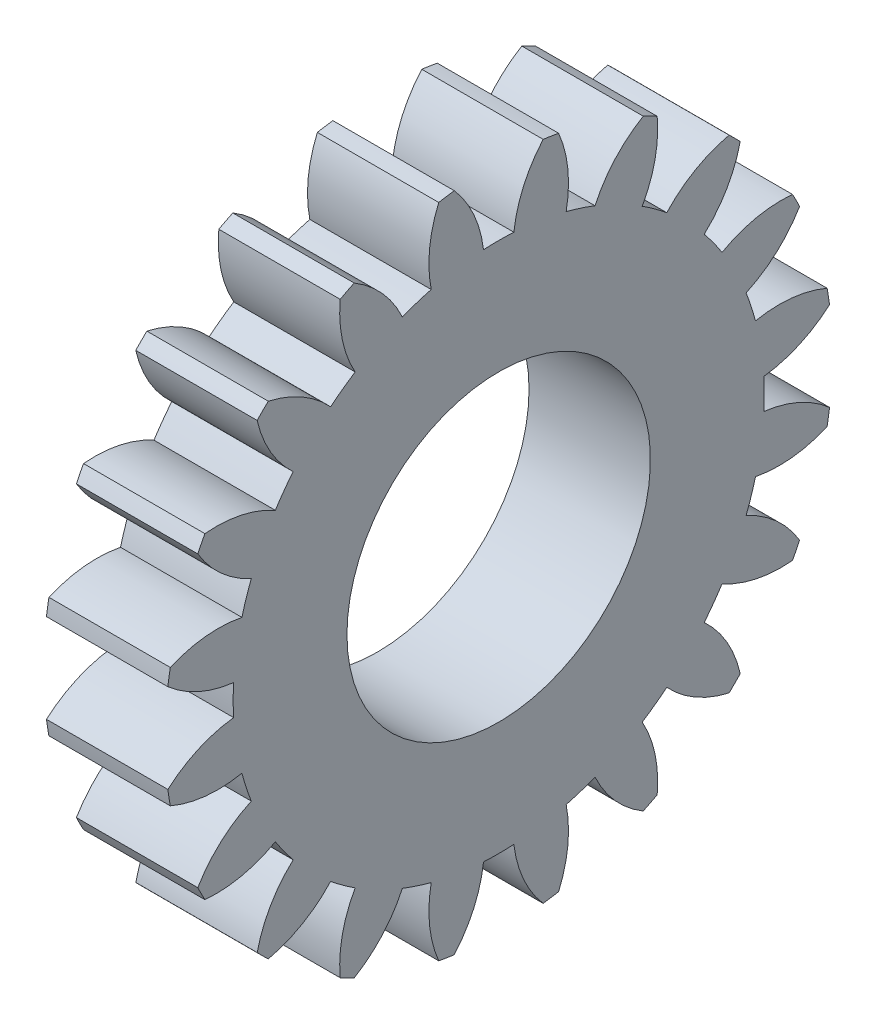
SolidWorks part; units mm, degrees
ref_plane "Plane1" through (0, 0, 0) normal (0, 0, 1) x (1, 0, 0)
ref_plane "Plane2" through (0, 0, 0) normal (0, 1, 0) x (1, 0, 0)
ref_plane "Plane3" through (0, 0, 0) normal (1, 0, 0) x (0, 0, -1)
sketch "HoldingSke" plane through (0, 0, 0) normal (0, 1, 0) x (1, 0, 0)
  line L0 (0, 0) -> (0.9397, -0.342)
  line L1 (-15, 0) -> (100, 0) construction
  line L2 (0, 0) -> (-2.1039, 2.3779)
  line L3 (0, 0) -> (-11.863, 4.5341)
  line L4 (0, 0) -> (8.1152, 2.9537)
  line L5 (0, 0) -> (-46.8476, -17.4728)
  line L6 (0, 0) -> (-3.3159, -2.2372)
  line L7 (-2.1039, 2.3779) -> (8.6586, 51.2059)
  line L8 (-76.2, 54.61) -> (-74.4, 54.61)
  line L9 (-71.009, 38.7566) -> (-53.1078, 45.2721)
  line L10 (-76.2, 71.12) -> (104.1128, 71.12)
  line L11 (0, 0) -> (-4, 0)
  line L12 (-76.2, 101.6) -> (-76.162, 101.6)
  line L13 (24.9733, 27.94) -> (52.9518, 28.4284)
  line L14 (24.9733, 27.94) -> (24.9743, 27.94)
  line L15 (24.9733, 27.94) -> (100.4006, 29.5858)
  line L16 (-63.627, -1) -> (-12.827, -1)
  circle A0 centre (0, 0) radius 5
  circle A1 centre (0, 0) radius 8.749
  circle A2 centre (0, 0) radius 37.5
  circle A3 centre (0, 0) radius 5
  dimension "MHD" = 17.498
  dimension "Hub_dia" = 75
  dimension "Bore" = 10
  dimension "MBD" = 10
  dimension "Num_teeth" = 20
  dimension "Pitch" = 1
  dimension "Overall_len" = 50
  dimension "Show_teeth" = 20
  dimension "Thickness" = 4
  dimension "OAL" = 50.0001
  dimension "T_dim" = 1.8
  dimension "Ap" = 20
  dimension "H" = 19.05
  dimension "Pitch_radius" = 180.3128
  dimension "Width" = 4
  dimension "Backlash" = 0.038
  dimension "Addendum_fac" = 1
  dimension "Dedendum_fac" = 1.25
  dimension "Clearance_fac" = 0.25
  dimension "Dedendum_add" = 0.001
  dimension "Module" = 1
sketch "BasProSke" plane through (0, 0, 0) normal (0, 1, 0) x (1, 0, 0)
  line L0 (-10, 0) -> (60, 0) construction
  line L1 (0, 0) -> (0, 11)
  line L2 (0, 0) -> (4, 0)
  line L3 (4, 0) -> (4, 11)
  line L4 (4, 11) -> (0, 11)
  dimension "Thickness" = 4
  dimension "Diameter" = 22
revolve "Base-Revolve" add sketch "BasProSke" angle 360 about L0
sketch "TooCutSke" plane through (0, 0, 0) normal (1, 0, 0) x (0, 0, -1)
  line L1 (0, 0) -> (0, 107) construction
  line L2 (0, 0) -> (-0.8511, 9.9637) construction
  line L3 (0, 0) -> (-3.1206, 19.7028) construction
  line L4 (-0.8511, 9.9637) -> (-1.5603, 9.8514) construction
  arc A0 (0.4999, 8.7347) -> (-0.4999, 8.7347) centre (0, 0) ccw
  arc A1 (1.4852, 10.9249) -> (-1.4852, 10.9249) centre (0, 0) ccw
  circle A2 centre (0, 0) radius 10 construction
  circle A3 centre (0, 0) radius 9.3969 construction
  arc A4 (-0.4999, 8.7347) -> (-1.4852, 10.9249) centre (-4.4722, 8.2645) ccw
  arc A5 (1.4852, 10.9249) -> (0.4999, 8.7347) centre (4.4722, 8.2645) ccw
  dimension "Root_dia" = 17.498
  dimension "Overcut_dia" = 22.0508
  dimension "Pitch_dia" = 20
  dimension "Base_dia" = 18.7939
  dimension "Flank_rad" = 4
  dimension "Half_ang" = 9
  dimension "Half_CT" = 0.7181
extrude "ToothCut" cut sketch "TooCutSke" along normal through all
fillet "Breaks" [suppressed] radius 0.02
fillet "RootFillets" [suppressed] radius 0.251
pattern_circular "TeethCuts" count 20 every 18 about axis through (-10, 0, 0) along (1, 0, 0) of "ToothCut", "RootFillets", "Breaks"
sketch "HubNeaOneSke" plane through (0, 0, 0) normal (-1, 0, 0) x (0, 0, 1)
  circle A0 centre (0, 0) radius 8.749
  dimension "Diameter" = 17.498
extrude "HubNearOne" [suppressed] add sketch "HubNeaOneSke" along normal blind 46.0001
sketch "HubNeaBotSke" plane through (0, 0, 0) normal (-1, 0, 0) x (0, 0, 1)
  circle A0 centre (0, 0) radius 8.749
  dimension "Diameter" = 17.498
extrude "HubNearBoth" [suppressed] add sketch "HubNeaBotSke" along normal blind 23
ref_plane "FarPln" through (4, 0, 0) normal (1, 0, 0) x (0, 0, -1)
sketch "HubFarSke" plane through (4, 0, 0) normal (1, 0, 0) x (0, 0, -1)
  circle A0 centre (0, 0) radius 8.749
  dimension "Diameter" = 17.498
extrude "HubFar" [suppressed] add sketch "HubFarSke" along normal blind 23
sketch "BorSke" plane through (0, 0, 0) normal (1, 0, 0) x (0, 0, -1)
  circle A0 centre (0, 0) radius 5
  dimension "Diameter" = 10
extrude "Bore" cut sketch "BorSke" along normal mid plane 100.0001
sketch "KeySke" plane through (0, 0, 0) normal (1, 0, 0) x (0, 0, -1)
  line L0 (-2, 0) -> (-2, 6.8)
  line L1 (-2, 6.8) -> (2, 6.8)
  line L2 (2, 6.8) -> (2, 0)
  line L3 (0, 0) -> (0, 34) construction
  line L4 (-2, 0) -> (2, 0)
  dimension "Width" = 4
  dimension "Offset" = 6.8
extrude "Keyway" [suppressed] cut sketch "KeySke" along normal mid plane 100.0001
pattern_circular "Keyway2" [suppressed] count 2 every 90 about axis through (-10, 0, 0) along (1, 0, 0)
sketch "Sketch1" plane through (4, 0, 0) normal (1, 0, 0) x (0, 0, -1)
  circle A0 centre (0, 0) radius 11
equation "' \"Module@HoldingSke\" = 6.35"
equation "' \"Num_teeth@HoldingSke\" = 12"
equation "' \"Ap@HoldingSke\" =  20"
equation "' \"Ap@HoldingSke\" = 20"
equation "' \"Width@HoldingSke\" = 0.5 * 25.4"
equation "' \"Hub_dia@HoldingSke\"= 1 * 25.4"
equation "' \"Hub_dia@HoldingSke\" = 1 * 25.4"
equation "' \"Overall_len@HoldingSke\" = 1.0 * 25.4"
equation "' \"Bore@HoldingSke\" = 0.75 * 25.4"
equation "' \"T_dim@HoldingSke\" = 0.1 * 25.4"
equation "' \"Width@KeySke\" = 0.25 * 25.4"
equation "' \"Show_teeth@HoldingSke\" = 13"
equation "' \"Backlash@HoldingSke\" = 0.009 * 25.4"
equation "' \"Addendum_fac@HoldingSke\" = 1.0"
equation "' \"Dedendum_fac@HoldingSke\" = 1.25"
equation "' \"Dedendum_add@HoldingSke\" = 0.00005 * 25.4"
equation "' \"Clearance_fac@HoldingSke\" = 0.25"
equation "\"Pitch@HoldingSke\" = 1 / \"Module@HoldingSke\""
equation "\"Overcut_dia@TooCutSke\" = (\"Num_teeth@HoldingSke\" + 2 * \"Addendum_fac@HoldingSke\") / \"Pitch@HoldingSke\" + 0.002 * 25.4"
equation "\"Pitch_dia@TooCutSke\" = \"Num_teeth@HoldingSke\" / \"Pitch@HoldingSke\""
equation "\"Base_dia@TooCutSke\" = \"Num_teeth@HoldingSke\" / \"Pitch@HoldingSke\" * cos((\"Ap@HoldingSke\"  * 3.14159265 / 180))"
equation "\"Root_dia@TooCutSke\" = (\"Num_teeth@HoldingSke\" + 2) / \"Pitch@HoldingSke\" - 2 * (\"Addendum_fac@HoldingSke\" + \"Dedendum_fac@HoldingSke\") / \"Pitch@HoldingSke\" - \"Dedendum_add@HoldingSke\" * 2"
equation "\"Half_ang@TooCutSke\" = 180 / \"Num_teeth@HoldingSke\""
equation "\"Half_CT@TooCutSke\" = \"Num_teeth@HoldingSke\" / \"Pitch@HoldingSke\" * sin((3.14159265 / 2 / \"Num_teeth@HoldingSke\")) / 2 - 7 * \"Backlash@HoldingSke\" / 4"
equation "\"Flank_rad@TooCutSke\" = \"Num_teeth@HoldingSke\" / \"Pitch@HoldingSke\" / 5"
equation "\"Radius@RootFillets\" = \"Clearance_fac@HoldingSke\" / \"Pitch@HoldingSke\" + \"Dedendum_add@HoldingSke\""
equation "\"Break_rad@Breaks\" = 0.02 / \"Pitch@HoldingSke\""
equation "\"Thickness@HoldingSke\" = \"Width@HoldingSke\""
equation "\"OAL@HoldingSke\" = \"Thickness@HoldingSke\""
equation "\"MHD@HoldingSke\" = (\"Num_teeth@HoldingSke\" + 2) / \"Pitch@HoldingSke\" - 2 * (\"Addendum_fac@HoldingSke\" + \"Dedendum_fac@HoldingSke\")  / \"Pitch@HoldingSke\" - \"Dedendum_add@HoldingSke\" * 2"
equation "\"MBD@HoldingSke\" = (\"Num_teeth@HoldingSke\" + 2) / \"Pitch@HoldingSke\" - 2 * (\"Addendum_fac@HoldingSke\" + \"Dedendum_fac@HoldingSke\")  / \"Pitch@HoldingSke\" - \"Dedendum_add@HoldingSke\" * 2 - 0.002 * 25.4"
equation "\"MHD@HoldingSke\" = ((sgn( \"MHD@HoldingSke\" - \"Hub_dia@HoldingSke\" )-1)*( \"MHD@HoldingSke\" - \"Hub_dia@HoldingSke\" ))/-2+ \"Hub_dia@HoldingSke\""
equation "\"MBD@HoldingSke\" = ((sgn( \"MBD@HoldingSke\" - \"Bore@HoldingSke\" )-1)*( \"MBD@HoldingSke\" - \"Bore@HoldingSke\" ))/-2+ \"Bore@HoldingSke\""
equation "\"OAL@HoldingSke\" = ((sgn( \"OAL@HoldingSke\" - \"Overall_len@HoldingSke\" )+1)*( \"OAL@HoldingSke\" - \"Overall_len@HoldingSke\" ))/2 + \"Overall_len@HoldingSke\" + 0.000002 * 25.4"
equation "\"Num_teeth@TeethCuts\" = int( \"Show_teeth@HoldingSke\" ) + 1"
equation "\"Num_teeth@TeethCuts\" = ((sgn( \"Num_teeth@TeethCuts\" - \"Num_teeth@HoldingSke\" )-1)*( \"Num_teeth@TeethCuts\" - \"Num_teeth@HoldingSke\" ))/-2+ \"Num_teeth@HoldingSke\""
equation "\"Num_teeth@TeethCuts\" = ((sgn( \"Num_teeth@TeethCuts\" - 2.0)+1)*( \"Num_teeth@TeethCuts\" - 2.0))/2 +2.0"
equation "\"Angle@TeethCuts\" = 360.0 / \"Num_teeth@HoldingSke\""
equation "\"Diameter@BasProSke\" = (\"Num_teeth@HoldingSke\" + 2 * \"Addendum_fac@HoldingSke\") / \"Pitch@HoldingSke\""
equation "\"Thickness@BasProSke\"  = \"Thickness@HoldingSke\""
equation "' \"Fillet_rad@BasProSke\" =  \"Thickness@HoldingSke\" * 0.05"
equation "' \"Fillet_rad@BasProSke\" = \"Thickness@HoldingSke\" * 0.05"
equation "\"MHD@HoldingSke\" = ((sgn( \"MHD@HoldingSke\" - \"Root_dia@TooCutSke\" )-1)*( \"MHD@HoldingSke\" - \"Root_dia@TooCutSke\" ))/-2+ \"Root_dia@TooCutSke\""
equation "\"Diameter@HubNeaOneSke\" = \"MHD@HoldingSke\""
equation "\"Length@HubNearOne\" = \"OAL@HoldingSke\" - \"Thickness@BasProSke\""
equation "\"Diameter@HubNeaBotSke\" = \"MHD@HoldingSke\""
equation "\"Length@HubNearBoth\" = ( \"OAL@HoldingSke\" - \"Thickness@BasProSke\" ) / 2.0"
equation "\"Thickness@FarPln\" = \"Thickness@BasProSke\""
equation "\"Diameter@HubFarSke\" = \"MHD@HoldingSke\""
equation "\"Length@HubFar\" = ( \"OAL@HoldingSke\" - \"Thickness@BasProSke\" ) / 2.0"
equation "\"Diameter@BorSke\" = \"MBD@HoldingSke\""
equation "\"D1@Bore\" = \"OAL@HoldingSke\" * 2.0"
equation "\"D1@Keyway\" = \"OAL@HoldingSke\" * 2.0"
equation "\"Offset@KeySke\" = \"T_dim@HoldingSke\" + \"MBD@HoldingSke\" / 2.0"
